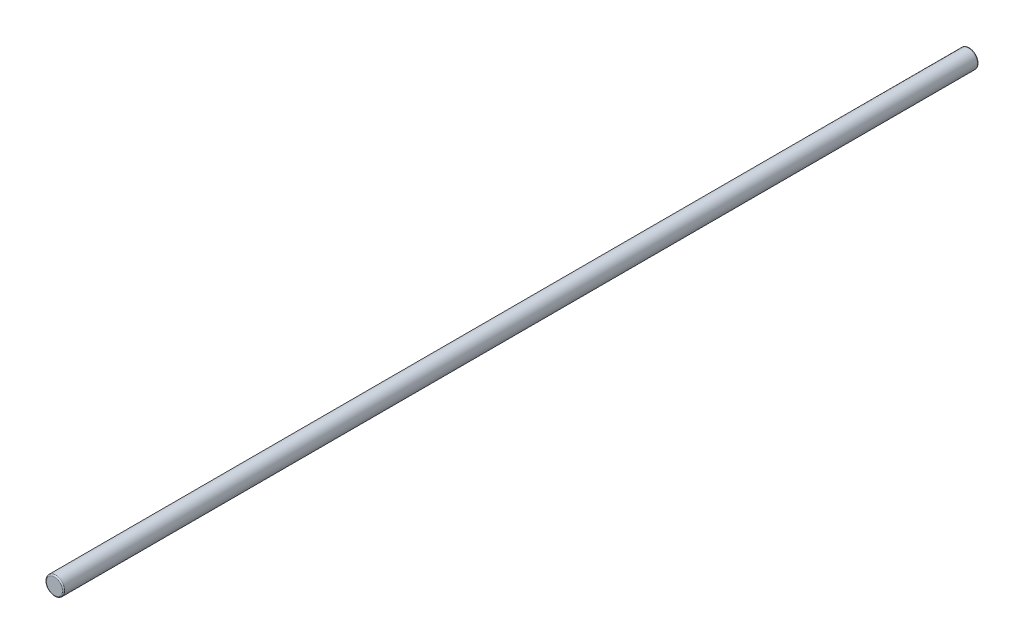
SolidWorks part; units mm, degrees
ref_plane "Alzado" through (0, 0, 0) normal (0, 0, 1) x (1, 0, 0)
ref_plane "Planta" through (0, 0, 0) normal (0, 1, 0) x (1, 0, 0)
ref_plane "Vista lateral" through (0, 0, 0) normal (1, 0, 0) x (0, 0, -1)
sketch "Croquis1" plane through (0, 0, 0) normal (0, 0, 1) x (1, 0, 0)
  circle A0 centre (0, 0) radius 4
  dimension "D1" = 8
extrude "Saliente-Extruir1" add sketch "Croquis1" along normal blind 400
fillet "Redondeo1" radius 0.5 2 edges at (4, 0, 0) (4, 0, 400)
